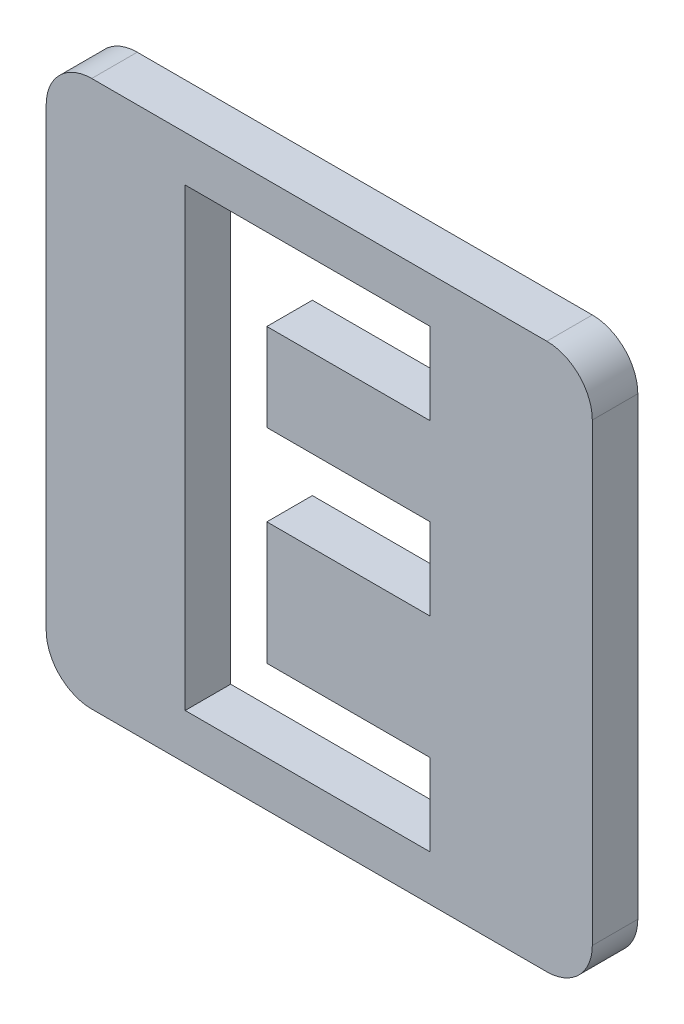
SolidWorks part; units mm, degrees
ref_plane "Front Plane" through (0, 0, 0) normal (0, 0, 1) x (1, 0, 0)
ref_plane "Top Plane" through (0, 0, 0) normal (0, 1, 0) x (1, 0, 0)
ref_plane "Right Plane" through (0, 0, 0) normal (1, 0, 0) x (0, 0, -1)
sketch "Sketch1" plane through (0, 0, 0) normal (0, 0, 1) x (1, 0, 0)
  line L1 (-50, 60) -> (50, 60)
  line L2 (-60, 50) -> (-60, -50)
  line L3 (-50, -60) -> (50, -60)
  line L4 (60, 50) -> (60, -50)
  line L5 (-60, 60) -> (60, -60) construction
  line L6 (-60, -60) -> (60, 60) construction
  arc A0 (-60, -50) -> (-50, -60) centre (-50, -50) ccw
  arc A1 (50, -60) -> (60, -50) centre (50, -50) ccw
  arc A2 (50, 60) -> (60, 50) centre (50, 50) cw
  arc A3 (-50, 60) -> (-60, 50) centre (-50, 50) ccw
  point P0 (0, 0)
  dimension "D3" = 10
  dimension "D1" = 120
  dimension "D2" = 120
extrude "Boss-Extrude1" add sketch "Sketch1" along normal blind 10 contours A3 L2 A0 L3 A1 L4 A2 L1
sketch "Sketch2" plane through (0, 0, 10) normal (0, 0, 1) x (1, 0, 0)
  line L0 (0, 0) -> (0, 40) construction
  line L1 (-50, 50) -> (50, 50) construction
  line L2 (-50, 50) -> (-50, -50) construction
  line L3 (-50, -50) -> (50, -50) construction
  line L4 (50, 50) -> (50, -50) construction
  line L5 (-50, 50) -> (50, -50) construction
  line L6 (-50, -50) -> (50, 50) construction
  line L7 (0, 40) -> (-40, 40) construction
  line L8 (-40, 40) -> (-40, 0) construction
  line L9 (-40, 0) -> (0, 0) construction
  line L11 (0, 20) -> (-20, 20) construction
  line L12 (-20, 40) -> (-20, 20) construction
  circle A0 centre (0, 40) radius 4 construction
  circle A1 centre (0, 20) radius 4 construction
  circle A2 centre (0, 0) radius 4 construction
  circle A3 centre (-20, 20) radius 4 construction
  circle A4 centre (-20, 40) radius 4 construction
  circle A5 centre (-40, 40) radius 4 construction
  circle A6 centre (0, 0) radius 4 construction
  circle A7 centre (20, 0) radius 4 construction
  circle A8 centre (40, 0) radius 4 construction
  circle A9 centre (40, 20) radius 4 construction
  circle A10 centre (40, 40) radius 4 construction
  circle A11 centre (20, 20) radius 4 construction
  circle A12 centre (0, 0) radius 4 construction
  circle A13 centre (0, -20) radius 4 construction
  circle A14 centre (0, -40) radius 4 construction
  circle A15 centre (20, -40) radius 4 construction
  circle A16 centre (40, -40) radius 4 construction
  circle A17 centre (20, -20) radius 4 construction
  circle A18 centre (0, 0) radius 4 construction
  circle A19 centre (-20, 0) radius 4 construction
  circle A20 centre (-40, 0) radius 4 construction
  circle A21 centre (-40, -20) radius 4 construction
  circle A22 centre (-40, -40) radius 4 construction
  circle A23 centre (-20, -20) radius 4 construction
  text T0 "E" font "Century Gothic" height 100
  point P0 (0, 0)
  point P55 (0, 0)
  dimension "D4" = 8
  dimension "D1" = 100
  dimension "D2" = 100
  dimension "D3" = 40
  dimension "D5" = 4
extrude "Cut-Extrude18" cut sketch "Sketch2" against normal blind 10
